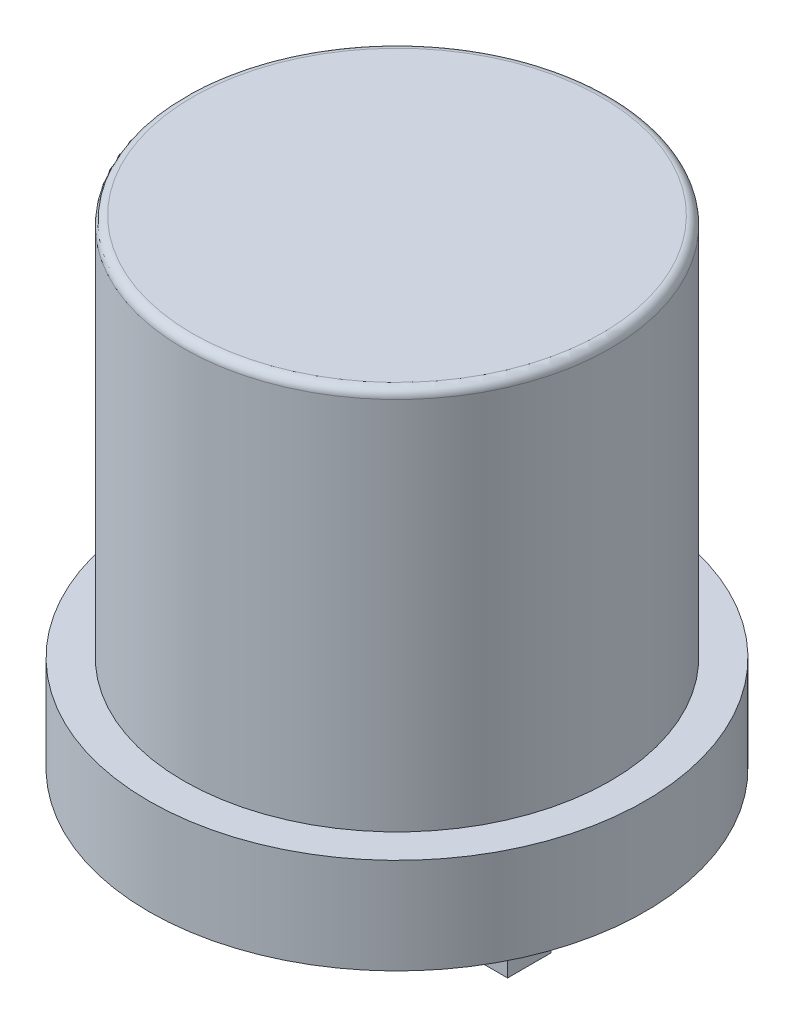
SolidWorks part; units mm, degrees
ref_plane "前视基准面" through (0, 0, 0) normal (0, 0, 1) x (1, 0, 0)
ref_plane "上视基准面" through (0, 0, 0) normal (0, 1, 0) x (1, 0, 0)
ref_plane "右视基准面" through (0, 0, 0) normal (1, 0, 0) x (0, 0, -1)
sketch "草图1" plane through (0, 0, 0) normal (0, 0, 1) x (1, 0, 0)
  line L0 (2.85, 1.1) -> (0, 1.1)
  line L1 (0, 1.1) -> (0, 0)
  line L2 (0, 0) -> (2.85, 0)
  line L3 (2.85, 0) -> (2.85, 1.1)
  line L4 (0, 1.1) -> (0, 0) construction
revolve "旋转1" add sketch "草图1" angle 360 about L4
sketch "草图2" plane through (0, 0, 0) normal (0, -1, 0) x (1, 0, 0)
  line L0 (1.52, -0.25) -> (1.02, -0.25)
  line L1 (1.02, -0.25) -> (1.02, 0.25)
  line L2 (1.02, 0.25) -> (1.52, 0.25)
  line L3 (1.52, 0.25) -> (1.52, -0.25)
extrude "凸台-拉伸1" add sketch "草图2" along normal blind 1.2
sketch "草图3" plane through (0, 0, 0) normal (0, -1, 0) x (1, 0, 0)
  line L0 (-1.52, 0.25) -> (-1.02, 0.25)
  line L1 (-1.02, 0.25) -> (-1.02, -0.25)
  line L2 (-1.02, -0.25) -> (-1.52, -0.25)
  line L3 (-1.52, -0.25) -> (-1.52, 0.25)
extrude "凸台-拉伸2" add sketch "草图3" along normal blind 1.2
sketch "草图4" plane through (0, 1.1, 0) normal (0, 1, 0) x (-1, 0, 0)
  circle A0 centre (0, 0) radius 2.45
extrude "凸台-拉伸3" add sketch "草图4" along normal blind 4.4
fillet "圆角1" radius 0.1 1 edges at (0, 5.5, 2.45)
sketch "草图6" plane through (0, 0, 0) normal (0, 0, 1) x (1, 0, 0)
  line L0 (-1.02, 3.853) -> (-0.1813, 3.853)
  line L1 (-1.52, 0.253) -> (-1.02, 0.253)
  line L2 (-1.52, 0.253) -> (-1.52, 3.853)
  line L3 (-1.52, 3.853) -> (-1.27, 3.853)
  line L4 (-1.02, 0.253) -> (-1.02, 3.853)
  line L5 (1.52, 0.253) -> (1.02, 0.253)
  line L6 (1.52, 0.253) -> (1.52, 4.753)
  line L7 (-0.4754, 4.753) -> (1.52, 4.753)
  line L8 (1.02, 0.253) -> (1.02, 3.5168)
  line L9 (-0.1813, 3.853) -> (-1.27, 4.753)
  line L10 (-1.27, 4.753) -> (-1.27, 3.853)
  line L12 (-0.4754, 4.753) -> (1.02, 3.5168)
  line L13 (1.02, -1.2) -> (1.02, 0) construction
  line L14 (1.52, -1.2) -> (1.52, 0) construction
  line L15 (-1.52, -1.2) -> (-1.52, 0) construction
  line L16 (-1.02, -1.2) -> (-1.02, 0) construction
  dimension "D1" = 3.6
  dimension "D2" = 4.5
extrude "切除-拉伸1" cut sketch "草图6" against normal mid plane 0.6
sketch "草图7" plane through (0, -1.2, 0) normal (0, -1, 0) x (1, 0, 0)
  circle A0 centre (-1.27, 0) radius 0.0716
  circle A1 centre (1.27, 0) radius 0.103
  dimension "D1" = 1.27
  dimension "D2" = 1.27
extrude "切除-拉伸2" cut sketch "草图7" against normal blind 1
